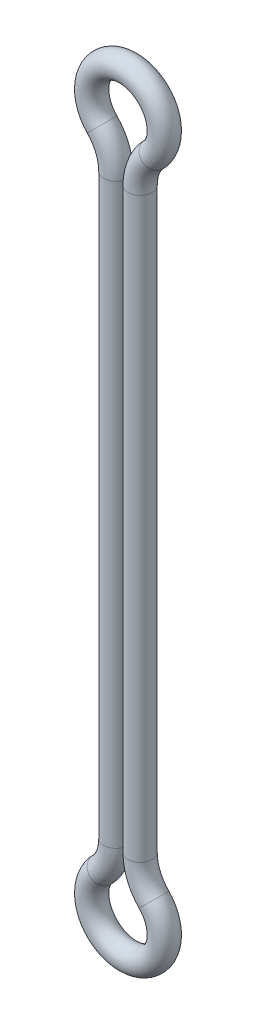
SolidWorks part; units mm, degrees
ref_plane "Front Plane" through (0, 0, 0) normal (0, 0, 1) x (1, 0, 0)
ref_plane "Top Plane" through (0, 0, 0) normal (0, 1, 0) x (1, 0, 0)
ref_plane "Right Plane" through (0, 0, 0) normal (1, 0, 0) x (0, 0, -1)
sketch "Sketch1" plane through (0, 0, 0) normal (0, 0, 1) x (1, 0, 0)
  line L0 (4, 9.798) -> (4, 105.202)
  line L2 (0, 105.202) -> (0, 9.798)
  line L3 (0, -55) -> (0, 55) construction
  line L4 (55, 0) -> (-55, 0) construction
  arc A0 (6.2857, 110.8009) -> (-2.2857, 110.8009) centre (2, 115) ccw
  arc A1 (-2.2857, 4.1991) -> (6.2857, 4.1991) centre (2, 0) ccw
  arc A2 (6.2857, 4.1991) -> (4, 9.798) centre (12, 9.798) cw
  arc A3 (-2.2857, 4.1991) -> (0, 9.798) centre (-8, 9.798) ccw
  arc A4 (4, 105.202) -> (6.2857, 110.8009) centre (12, 105.202) cw
  arc A5 (0, 105.202) -> (-2.2857, 110.8009) centre (-8, 105.202) ccw
  point P17 (4, 109.3431)
  point P20 (0, 109.3431)
  dimension "D3" = 127
  dimension "D4" = 12
  dimension "D5" = 6
  dimension "D6" = 8
  dimension "D1" = 4
  dimension "D2" = 2
ref_plane "Plane1" through (0, 10, 0) normal (0, 1, 0) x (-1, 0, 0)
sketch "Sketch2" plane through (0, 10, 0) normal (0, 1, 0) x (-1, 0, 0)
  circle A0 centre (0, 0) radius 2
  dimension "D1" = 4
sweep "Sweep1" add profiles "Sketch2" path "Sketch1"
